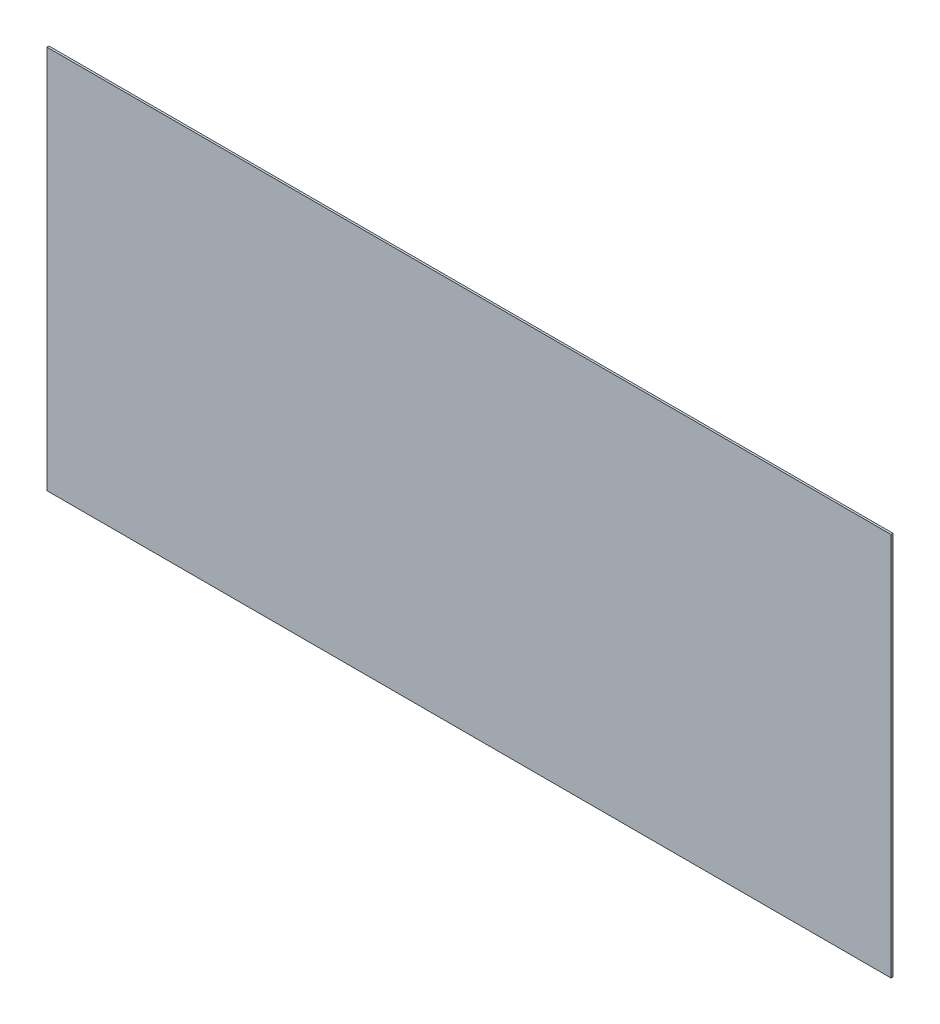
SolidWorks part; units mm, degrees
ref_plane "Front Plane" through (0, 0, 0) normal (0, 0, 1) x (1, 0, 0)
ref_plane "Top Plane" through (0, 0, 0) normal (0, 1, 0) x (1, 0, 0)
ref_plane "Right Plane" through (0, 0, 0) normal (1, 0, 0) x (0, 0, -1)
other "Configuration Table"
sketch "Sketch1" plane through (0, 0, 0) normal (0, 0, 1) x (1, 0, 0)
  line L1 (714, 403) -> (1338, 403)
  line L2 (714, 403) -> (714, 687)
  line L3 (714, 687) -> (1338, 687)
  line L4 (1338, 403) -> (1338, 687)
extrude "STORE_panel_bos_bant_1" add sketch "Sketch1" along normal blind 1.5 from offset 38.5 separate body
